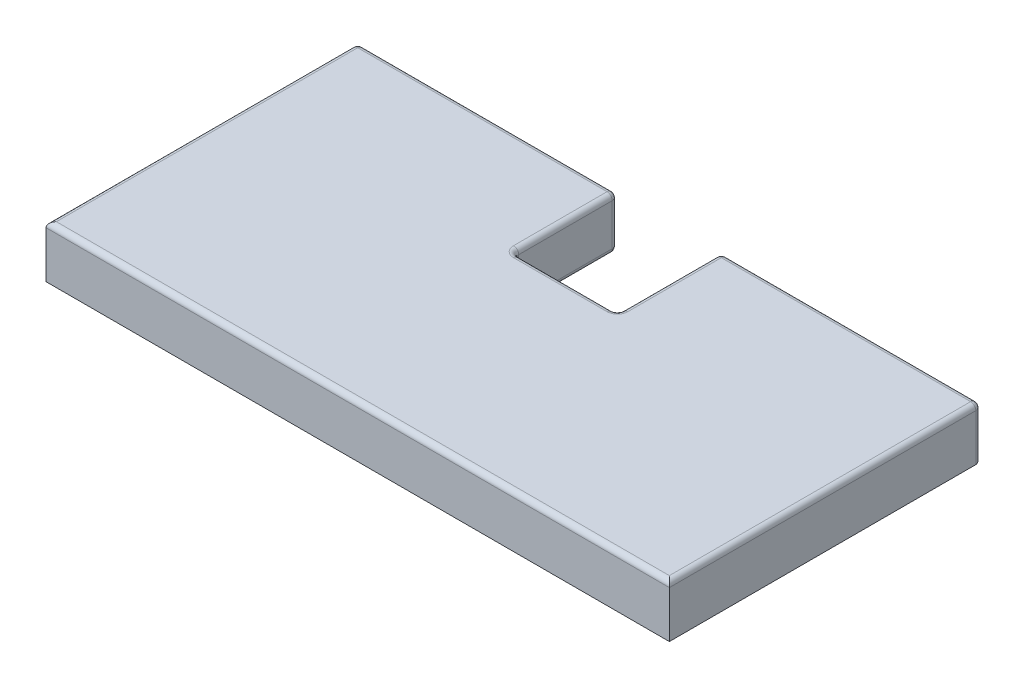
SolidWorks part; units mm, degrees
ref_plane "Front Plane" through (0, 0, 0) normal (0, 0, 1) x (1, 0, 0)
ref_plane "Top Plane" through (0, 0, 0) normal (0, 1, 0) x (1, 0, 0)
ref_plane "Right Plane" through (0, 0, 0) normal (1, 0, 0) x (0, 0, -1)
sketch "Sketch1" plane through (0, 0, 0) normal (0, 1, 0) x (1, 0, 0)
  line L1 (-516.0526, 370.5409) -> (-456.0526, 370.5409)
  line L2 (-516.0526, 370.5409) -> (-516.0526, 340.5409)
  line L3 (-516.0526, 340.5409) -> (-456.0526, 340.5409)
  line L4 (-456.0526, 370.5409) -> (-456.0526, 340.5409)
  dimension "D1" = 60
  dimension "D2" = 30
extrude "Boss-Extrude1" add sketch "Sketch1" along normal blind 5 contours L3 L4 L1 L2
sketch "Sketch2" plane through (0, 0, -370.5409) normal (0, 0, -1) x (-1, 0, 0)
  line L0 (516.0526, 5) -> (456.0526, 5) construction
  line L1 (481.0526, 5) -> (491.0526, 5)
  line L2 (481.0526, 5) -> (481.0526, 0)
  line L3 (481.0526, 0) -> (491.0526, 0)
  line L4 (491.0526, 5) -> (491.0526, 0)
  line L5 (516.0526, 0) -> (456.0526, 0) construction
  line L6 (456.0526, 5) -> (456.0526, 0) construction
  dimension "D1" = 10
  dimension "D2" = 25
  dimension "D3" = 5
extrude "Cut-Extrude1" cut sketch "Sketch2" against normal blind 10 contours L2 L3 L4 L1
fillet "Fillet1" radius 0.5 19 edges at (-491.0526, 0, -365.5409) (-481.0526, 0, -365.5409) (-491.0526, 2.5, -370.5409) (-481.0526, 2.5, -370.5409) (-486.0526, 5, -360.5409) (-491.0526, 2.5, -360.5409) (-486.0526, 0, -360.5409) (-481.0526, 2.5, -360.5409) (-481.0526, 5, -365.5409) (-491.0526, 5, -365.5409) (-468.5526, 0, -370.5409) (-503.5526, 0, -370.5409) (-516.0526, 5, -355.5409) (-486.0526, 5, -340.5409) (-456.0526, 5, -355.5409) (-468.5526, 5, -370.5409) (-503.5526, 5, -370.5409) (-516.0526, 2.5, -370.5409) (-456.0526, 2.5, -370.5409)
equation "\"BaseWidth\"= 60"
equation "\"BaseLength\"= 30"
equation "\"D1@Sketch1\"=\"BaseWidth\""
equation "\"D2@Sketch1\"=\"BaseLength\""
equation "\"BaseHeight\"= 5"
equation "\"D1@Boss-Extrude1\"=\"BaseHeight\""
equation "\"BeamWidth\"= 10"
equation "\"D1@Sketch2\"=\"BeamWidth\""
equation "\"D2@Sketch2\"=(\"BaseWidth\"-\"BeamWidth\")/2"
equation "\"BeamLength\"= 10"
equation "\"D1@Cut-Extrude1\"=\"BeamLength\""
